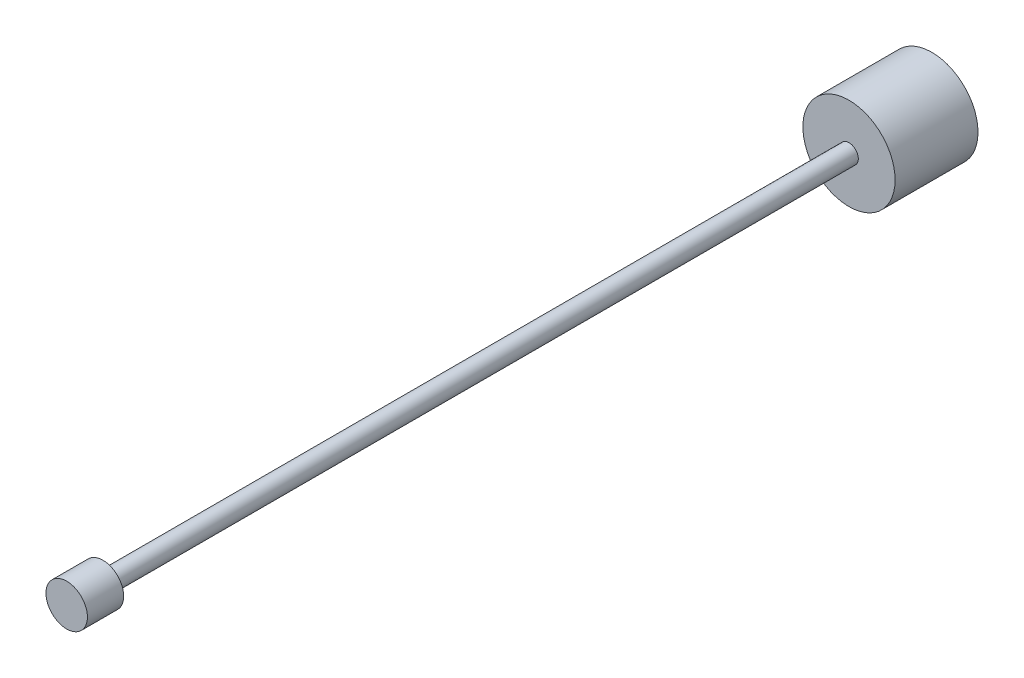
SolidWorks part; units mm, degrees
ref_plane "Front Plane" through (0, 0, 0) normal (0, 0, 1) x (1, 0, 0)
ref_plane "Top Plane" through (0, 0, 0) normal (0, 1, 0) x (1, 0, 0)
ref_plane "Right Plane" through (0, 0, 0) normal (1, 0, 0) x (0, 0, -1)
sketch "Sketch1" plane through (0, 0, 0) normal (0, 0, 1) x (1, 0, 0)
  circle A0 centre (0, 0) radius 8.9
  dimension "D1" = 17.8
extrude "Boss-Extrude1" add sketch "Sketch1" along normal blind 16 contours A0
sketch "Sketch2" plane through (0, 0, 16) normal (0, 0, 1) x (1, 0, 0)
  circle A0 centre (0, 0) radius 1.8
  dimension "D1" = 3.6
extrude "Boss-Extrude2" add sketch "Sketch2" along normal blind 144 separate body contours A0
sketch "Sketch4" plane through (0, 0, 160) normal (0, 0, 1) x (1, 0, 0)
  circle A0 centre (0, 0) radius 4
  dimension "D1" = 8
extrude "Boss-Extrude3" add sketch "Sketch4" along normal blind 7 contours A0
